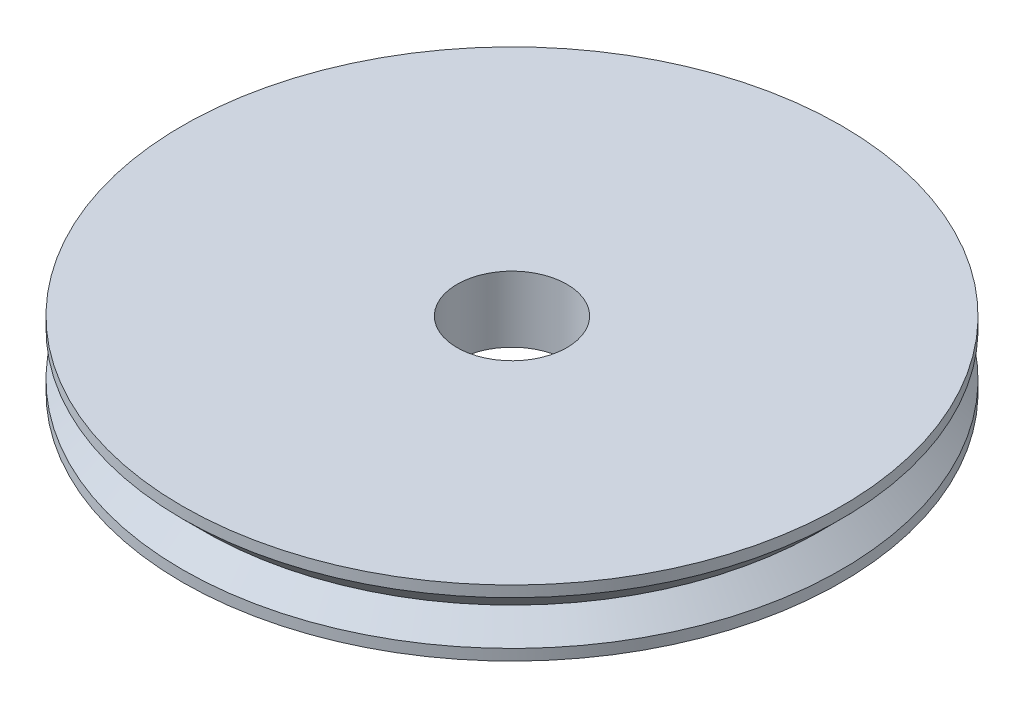
SolidWorks part; units mm, degrees
ref_plane "Front Plane" through (0, 0, 0) normal (0, 0, 1) x (1, 0, 0)
ref_plane "Top Plane" through (0, 0, 0) normal (0, 1, 0) x (1, 0, 0)
ref_plane "Right Plane" through (0, 0, 0) normal (1, 0, 0) x (0, 0, -1)
sketch "Sketch1" plane through (0, 0, 0) normal (0, 0, 1) x (1, 0, 0)
  line L0 (-2.5, 0) -> (-2.5, 3)
  line L1 (-2.5, 3) -> (-15, 3)
  line L2 (-15, 3) -> (-15, 2.5)
  line L3 (-15, 2.5) -> (-14, 1.5)
  line L4 (-14, 1.5) -> (-15, 0.5)
  line L5 (-15, 0.5) -> (-15, 0)
  line L6 (-2.5, 0) -> (-15, 0)
  line L7 (0, 0) -> (0, 9.0584) construction
  dimension "D1" = 2.5
  dimension "D2" = 0.5
  dimension "D3" = 0.5
  dimension "D4" = 1
  dimension "D5" = 1
  dimension "D6" = 1
  dimension "D7" = 15
  dimension "D8" = 0
revolve "Revolve1" add sketch "Sketch1" angle 360 about L7
